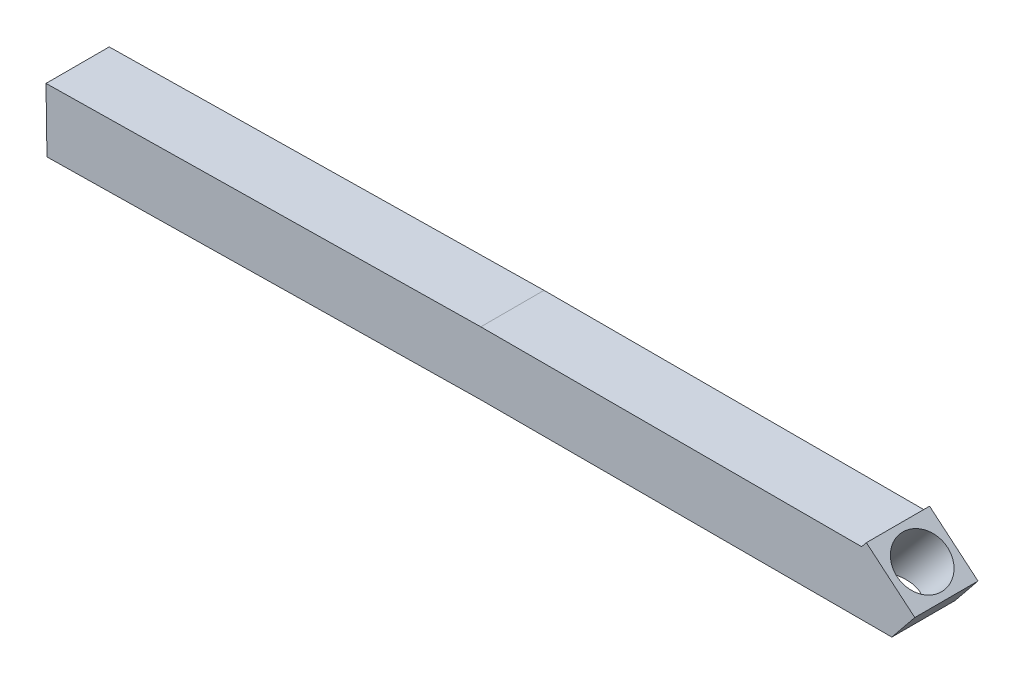
SolidWorks part; units mm, degrees
ref_plane "Front Plane" through (0, 0, 0) normal (0, 0, 1) x (1, 0, 0)
ref_plane "Top Plane" through (0, 0, 0) normal (0, 1, 0) x (1, 0, 0)
ref_plane "Right Plane" through (0, 0, 0) normal (1, 0, 0) x (0, 0, -1)
sketch "Sketch1" plane through (0, 0, 0) normal (0, 0, 1) x (1, 0, 0)
  line L0 (-70.4062, -77.7101) -> (-55.3432, -77.7101)
  line L1 (-55.3432, -77.7101) -> (-55.1558, -77.478)
  line L2 (-70.4062, -77.7101) -> (-70.3683, -80.2098)
  line L3 (-70.3683, -80.2098) -> (-54.149, -80.2098)
  line L4 (-54.149, -80.2098) -> (-53.2406, -79.0849)
  line L5 (-53.2406, -79.0849) -> (-55.1558, -77.478)
  line L8 (-70.4062, -77.7101) -> (-70.3683, -80.2098) construction
  dimension "D1" = 16.2175
  dimension "D2" = 2.4997
  dimension "D4" = 2.5
extrude "Boss-Extrude1" add sketch "Sketch1" along normal blind 2.5
sketch "Sketch2" plane through (-60.9395, -72.6249, 0) normal (0.6428, 0.766, 0) x (0, 0, -1)
  line L0 (-2.5, -10.0501) -> (-2.5, -7.5501) construction
  circle A0 centre (-1.25, -8.8001) radius 1
  point P4 (-2.5, -8.8001)
  dimension "D1" = 2
extrude "Cut-Extrude1" cut sketch "Sketch2" against normal blind 4.5
sketch "Sketch3" plane through (-71.5657, -1.0829, 0) normal (-0.9999, -0.0151, 0) x (0, 0, 1)
  line L0 (0, -76.6359) -> (0, -79.1359) construction
  line L1 (2.5, -79.1359) -> (0, -79.1359) construction
  circle A0 centre (1.25, -77.8859) radius 1
  point P4 (0, -77.8859)
  point P7 (1.25, -79.1359)
  dimension "D1" = 2
extrude "Cut-Extrude2" cut sketch "Sketch3" against normal blind 9.5
sketch "Sketch5" plane through (-71.5657, -1.0829, 0) normal (-0.9999, -0.0151, 0) x (0, 0, 1)
  line L0 (0, -77.8859) -> (2.5, -77.8859) construction
  line L1 (0, -76.6359) -> (0, -79.1359) construction
  line L2 (2.5, -76.6359) -> (2.5, -79.1359) construction
  line L3 (1.25, -76.6359) -> (1.25, -79.1359) construction
  line L4 (2.5, -76.6359) -> (0, -76.6359) construction
  line L5 (2.5, -79.1359) -> (0, -79.1359) construction
  circle A0 centre (1.25, -77.8859) radius 1
extrude "Boss-Extrude2" add sketch "Sketch5" against normal blind 9.5
sketch "Sketch6" plane through (-71.5657, -1.0829, 0) normal (-0.9999, -0.0151, 0) x (0, 0, 1)
  line L0 (0, -76.6359) -> (2.5, -76.6359)
  line L1 (0, -76.6359) -> (0, -79.1359)
  line L2 (2.5, -76.6359) -> (2.5, -79.1359)
  line L3 (0, -79.1359) -> (2.5, -79.1359)
  line L4 (2.5, -79.1359) -> (0, -79.1359) construction
  dimension "D1" = 0
sketch "Sketch7" plane through (-71.5657, -1.0829, 0) normal (-0.9999, -0.0151, 0) x (0, 0, 1)
  line L0 (0, -76.6359) -> (2.5, -76.6359)
  line L1 (0, -76.6359) -> (0, -79.1229)
  line L2 (2.5, -76.6359) -> (2.5, -79.1229)
  line L3 (0, -79.1229) -> (2.5, -79.1229)
extrude "Boss-Extrude5" add sketch "Sketch7" along normal blind 17
sketch "Sketch8" plane through (-88.5637, -1.3401, 0) normal (-0.9999, -0.0151, 0) x (0, 0, 1)
  line L0 (0, -77.8859) -> (2.5, -77.8859) construction
  line L1 (0, -76.6359) -> (0, -79.1359) construction
  line L2 (2.5, -76.6359) -> (2.5, -79.1359) construction
  line L3 (1.25, -76.6359) -> (1.25, -79.1359) construction
  line L4 (0, -76.6359) -> (2.5, -76.6359) construction
  line L5 (0, -79.1359) -> (2.5, -79.1359) construction
  circle A0 centre (1.25, -77.8859) radius 1
  dimension "D1" = 2
extrude "Cut-Extrude3" cut sketch "Sketch8" against normal blind 9.5
sketch "Sketch9" plane through (-88.5637, -1.3401, 0) normal (-0.9999, -0.0151, 0) x (0, 0, 1)
  line L0 (0, -76.6359) -> (2.5, -76.6359)
  line L1 (0, -76.6359) -> (0, -79.1468)
  line L2 (2.5, -76.6359) -> (2.5, -79.1468)
  line L3 (0, -79.1468) -> (2.5, -79.1468)
extrude "Cut-Extrude4" cut sketch "Sketch9" against normal blind 10.5
sketch "Sketch10" plane through (-78.0649, -1.1813, 0) normal (-0.9999, -0.0151, 0) x (0, 0, 1)
  line L0 (0, -77.8859) -> (2.5, -77.8859) construction
  line L1 (0, -76.6359) -> (0, -79.1359) construction
  line L2 (2.5, -76.6359) -> (2.5, -79.1359) construction
  line L3 (1.25, -76.6359) -> (1.25, -79.1359) construction
  line L4 (0, -76.6359) -> (2.5, -76.6359) construction
  line L5 (0, -79.1359) -> (2.5, -79.1359) construction
  circle A0 centre (1.25, -77.8859) radius 1
  dimension "D1" = 2
extrude "Cut-Extrude5" cut sketch "Sketch10" against normal blind 4.5
sketch "Sketch11" plane through (-78.0649, -1.1813, 0) normal (-0.9999, -0.0151, 0) x (0, 0, 1)
  line L0 (0, -77.8859) -> (2.5, -77.8859) construction
  line L1 (0, -76.6359) -> (0, -79.1359) construction
  line L2 (2.5, -76.6359) -> (2.5, -79.1359) construction
  line L3 (1.25, -76.6359) -> (1.25, -79.1359) construction
  line L4 (0, -76.6359) -> (2.5, -76.6359) construction
  line L5 (0, -79.1359) -> (2.5, -79.1359) construction
  circle A0 centre (1.25, -77.8859) radius 1
extrude "Boss-Extrude6" add sketch "Sketch11" against normal blind 4.5
sketch "Sketch12" plane through (-78.0649, -1.1813, 0) normal (-0.9999, -0.0151, 0) x (0, 0, 1)
  line L0 (0, -77.8859) -> (2.5, -77.8859) construction
  line L1 (0, -76.6359) -> (0, -79.1359) construction
  line L2 (2.5, -76.6359) -> (2.5, -79.1359) construction
  line L3 (1.25, -76.6359) -> (1.25, -79.1359) construction
  line L4 (0, -76.6359) -> (2.5, -76.6359) construction
  line L5 (0, -79.1359) -> (2.5, -79.1359) construction
  circle A0 centre (1.25, -77.8859) radius 1
  dimension "D1" = 2
extrude "Cut-Extrude6" cut sketch "Sketch12" against normal blind 4
sketch "Sketch13" plane through (-78.0649, -1.1813, 0) normal (-0.9999, -0.0151, 0) x (0, 0, 1)
  line L3 (0, -76.6359) -> (2.5, -76.6359)
  line L4 (0, -76.6359) -> (0, -79.1359)
  line L5 (0, -79.1359) -> (2.5, -79.1359)
  line L6 (2.5, -76.6359) -> (2.5, -79.1359)
extrude "Cut-Extrude7" cut sketch "Sketch13" against normal up to vertex (6.5 mm away) up to point (-70.4062, -77.7101, 0)
sketch "Sketch14" plane through (-71.5657, -1.0829, 0) normal (-0.9999, -0.0151, 0) x (0, 0, 1)
  line L1 (0, -76.6359) -> (2.5, -76.6359)
  line L2 (0, -76.6359) -> (0, -79.1359)
  line L3 (0, -79.1359) -> (2.5, -79.1359)
  line L4 (2.5, -76.6359) -> (2.5, -79.1359)
extrude "Boss-Extrude7" add sketch "Sketch14" along normal blind 6.5
sketch "Sketch15" plane through (-78.0649, -1.1813, 0) normal (-0.9999, -0.0151, 0) x (0, 0, 1)
  line L0 (0, -77.8859) -> (2.5, -77.8859) construction
  line L1 (0, -76.6359) -> (0, -79.1359) construction
  line L2 (2.5, -76.6359) -> (2.5, -79.1359) construction
  line L3 (1.25, -76.6359) -> (1.25, -79.1359) construction
  line L4 (0, -76.6359) -> (2.5, -76.6359) construction
  line L5 (0, -79.1359) -> (2.5, -79.1359) construction
  circle A0 centre (1.25, -77.8859) radius 1
  dimension "D1" = 2
extrude "Cut-Extrude8" cut sketch "Sketch15" against normal blind 5
sketch "Sketch16" plane through (-78.0649, -1.1813, 0) normal (-0.9999, -0.0151, 0) x (0, 0, 1)
  circle A0 centre (1.25, -77.8859) radius 1
extrude "Boss-Extrude8" add sketch "Sketch16" against normal blind 5
sketch "Sketch17" plane through (-78.0649, -1.1813, 0) normal (-0.9999, -0.0151, 0) x (0, 0, 1)
  line L0 (0, -76.6359) -> (2.5, -76.6359)
  line L1 (0, -76.6359) -> (0, -79.1359)
  line L2 (2.5, -76.6359) -> (2.5, -79.1359)
  line L3 (0, -79.1359) -> (2.5, -79.1359)
  line L4 (0, -79.1359) -> (2.5, -79.1359) construction
  dimension "D1" = 0
extrude "Boss-Extrude9" add sketch "Sketch17" along normal blind 17
sketch "Sketch18" plane through (-95.063, -1.4385, 0) normal (-0.9999, -0.0151, 0) x (0, 0, 1)
  line L0 (0, -77.8859) -> (2.5, -77.8859) construction
  line L1 (0, -76.6359) -> (0, -79.1359) construction
  line L2 (2.5, -76.6359) -> (2.5, -79.1359) construction
  line L3 (1.25, -76.6359) -> (1.25, -79.1359) construction
  line L4 (0, -76.6359) -> (2.5, -76.6359) construction
  line L5 (0, -79.1359) -> (2.5, -79.1359) construction
  circle A0 centre (1.25, -77.8859) radius 1
  dimension "D1" = 2
extrude "Cut-Extrude9" cut sketch "Sketch18" against normal blind 5
sketch "Sketch19" plane through (-95.063, -1.4385, 0) normal (-0.9999, -0.0151, 0) x (0, 0, 1)
  line L0 (0, -76.6359) -> (2.5, -76.6359)
  line L1 (0, -76.6359) -> (0, -79.1359)
  line L2 (2.5, -76.6359) -> (2.5, -79.1359)
  line L3 (0, -79.1359) -> (2.5, -79.1359)
  line L4 (0, -79.1359) -> (2.5, -79.1359) construction
  dimension "D1" = 0
extrude "Cut-Extrude10" cut sketch "Sketch19" against normal blind 6.3
sketch "Sketch20" plane through (-88.7637, -1.3431, 0) normal (-0.9999, -0.0151, 0) x (0, 0, 1)
  line L0 (1.25, -76.6359) -> (1.25, -79.1359) construction
  line L1 (0, -76.6359) -> (2.5, -76.6359) construction
  line L2 (0, -79.1359) -> (2.5, -79.1359) construction
  line L3 (0, -77.8859) -> (2.5, -77.8859) construction
  line L4 (0, -76.6359) -> (0, -79.1359) construction
  line L5 (2.5, -76.6359) -> (2.5, -79.1359) construction
  circle A0 centre (1.25, -77.8859) radius 1
  dimension "D1" = 2
extrude "Cut-Extrude11" cut sketch "Sketch20" against normal blind 5
